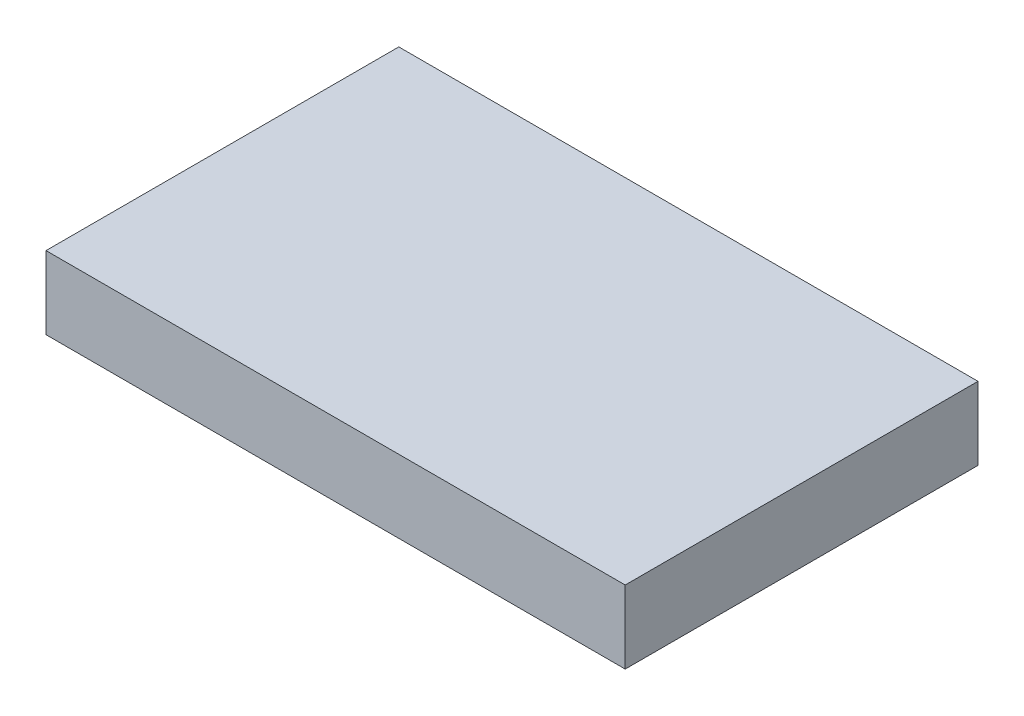
SolidWorks part; units mm, degrees
ref_plane "前视基准面" through (0, 0, 0) normal (0, 0, 1) x (1, 0, 0)
ref_plane "上视基准面" through (0, 0, 0) normal (0, 1, 0) x (1, 0, 0)
ref_plane "右视基准面" through (0, 0, 0) normal (1, 0, 0) x (0, 0, -1)
sketch "草图1" plane through (0, 0, 0) normal (0, 1, 0) x (1, 0, 0)
  line L1 (-9.3284, 4.098) -> (23.6716, 4.098)
  line L2 (-9.3284, 4.098) -> (-9.3284, -16.002)
  line L3 (-9.3284, -16.002) -> (23.6716, -16.002)
  line L4 (23.6716, 4.098) -> (23.6716, -16.002)
  dimension "D1" = 20.1
  dimension "D2" = 33
extrude "凸台-拉伸1" add sketch "草图1" along normal blind 4.15
